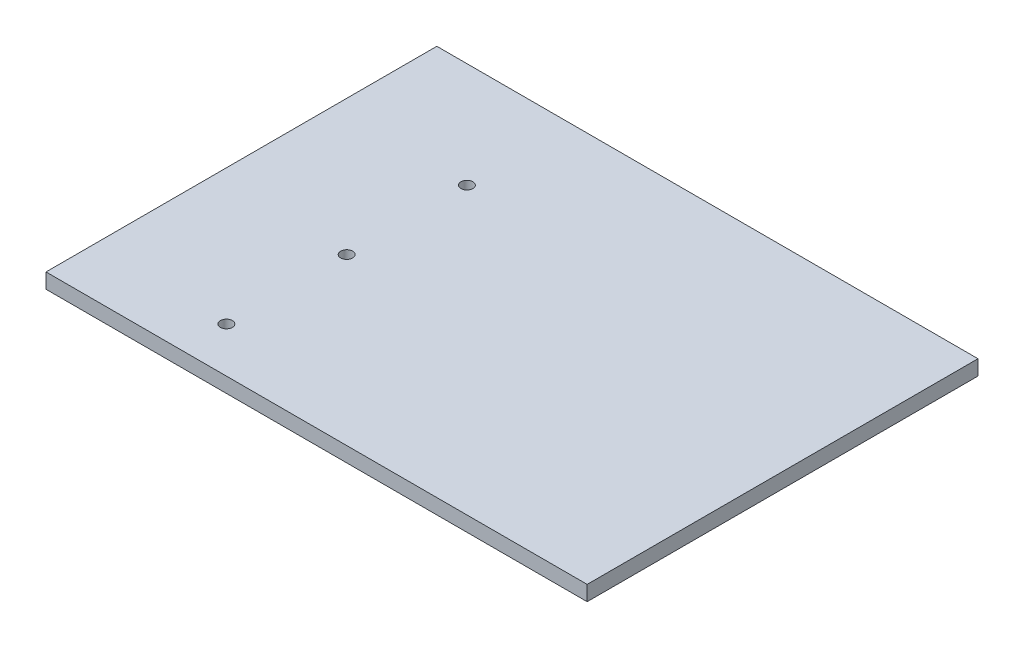
SolidWorks part; units mm, degrees
material "ASTM A36 Steel"
ref_plane "Front Plane" through (0, 0, 0) normal (0, 0, 1) x (1, 0, 0)
ref_plane "Top Plane" through (0, 0, 0) normal (0, 1, 0) x (1, 0, 0)
ref_plane "Right Plane" through (0, 0, 0) normal (1, 0, 0) x (0, 0, -1)
sketch "Sketch1" plane through (0, 0, 0) normal (0, 1, 0) x (1, 0, 0)
  line L1 (-228.6, 165.1) -> (228.6, 165.1)
  line L2 (-228.6, 165.1) -> (-228.6, -165.1)
  line L3 (-228.6, -165.1) -> (228.6, -165.1)
  line L4 (228.6, 165.1) -> (228.6, -165.1)
  dimension "D1" = 330.2
  dimension "D2" = 457.2
  dimension "D3" = 165.1
  dimension "D4" = 228.6
extrude "Boss-Extrude1" add sketch "Sketch1" along normal blind 12.7
hole_wizard "3/8 Clearance Hole1" positions "Sketch2" profile "Sketch3" hole size "3/8" standard "ANSI Inch" end condition through all
sketch "Sketch2" plane through (0, 12.7, -165.1) normal (0, 1, 0) x (1, 0, 0)
  point P0 (-114.3, -88.9)
  point P1 (-114.3, -190.5)
  point P2 (-114.3, -292.1)
sketch "Sketch3" plane through (-114.3, 12.7, -76.2) normal (1, 0, 0) x (0, 0, 1)
  line L0 (0, 0) -> (0, 12.7)
  line L1 (0, 12.7) -> (5.0419, 12.7)
  line L2 (5.0419, 12.7) -> (5.0419, 0)
  line L5 (5.0419, 0) -> (0, 0)
  line L11 (0, -6.35) -> (0, 107.95) construction
  dimension "Thru Hole Dia." = 10.0838
  dimension "Thru Hole Depth" = 12.7
equation "\"Var1\"=13"
equation "\"D1@Sketch1\"=\"Var1\""
equation "\"Var2\"=18"
equation "\"D2@Sketch1\"=\"Var2\""
equation "\"D3@Sketch1\"=\"Var1\"/2"
equation "\"D4@Sketch1\"=\"Var2\"/2"
equation "\"t\"= 0.25"
equation "\"#H\"= 3"
equation "\"#V\"= 7"
equation "\"DH\"= ( \"Var1\" - 1 + \"t\" ) / \"#H\""
equation "\"DV\"= ( \"Var2\" + \"t\" - 2 ) / \"#V\""
